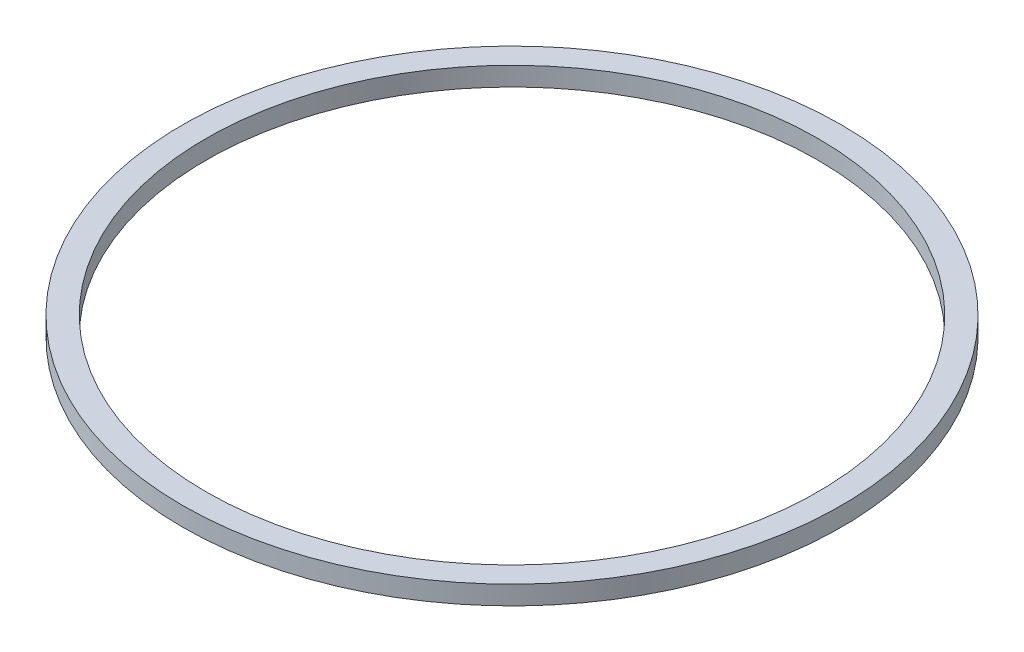
SolidWorks part; units mm, degrees
material "AISI 304"
ref_plane "Front Plane" through (0, 0, 0) normal (0, 0, 1) x (1, 0, 0)
ref_plane "Top Plane" through (0, 0, 0) normal (0, 1, 0) x (1, 0, 0)
ref_plane "Right Plane" through (0, 0, 0) normal (1, 0, 0) x (0, 0, -1)
sketch "Sketch1" plane through (0, 0, 0) normal (0, 1, 0) x (1, 0, 0)
  circle A0 centre (0, 0) radius 325
  circle A1 centre (0, 0) radius 350
  dimension "D1" = 650
  dimension "D2" = 700
extrude "Boss-Extrude1" add sketch "Sketch1" along normal mid plane 20
